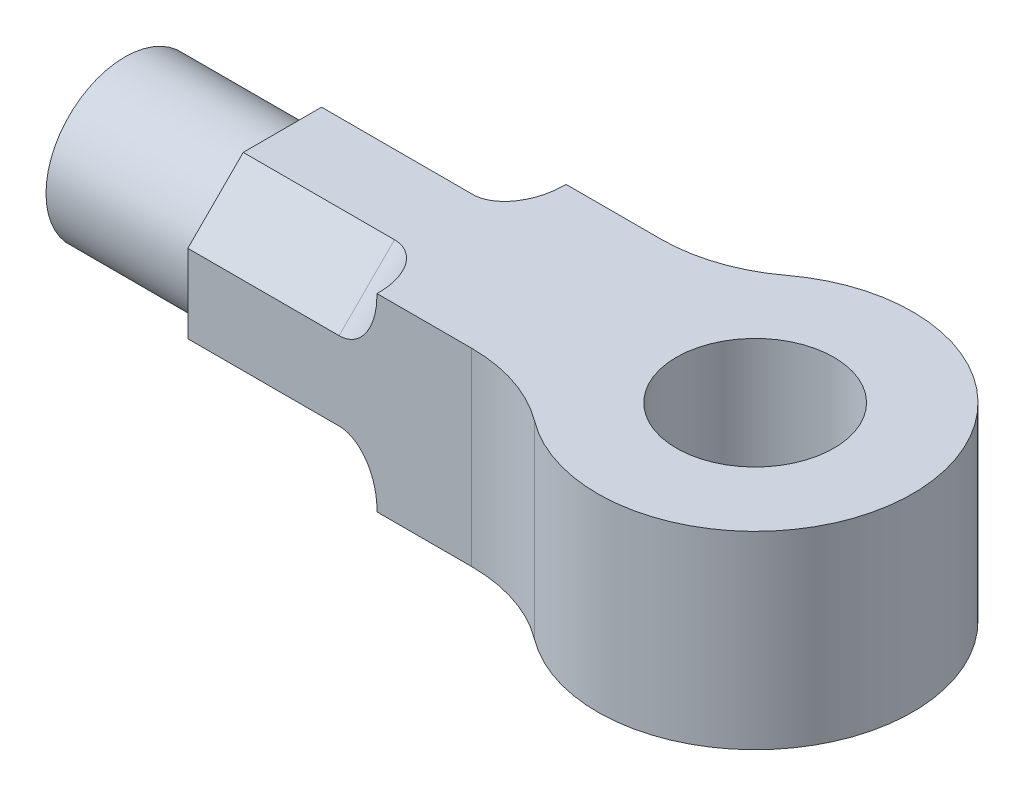
SolidWorks part; units mm, degrees
ref_plane "Front Plane" through (0, 0, 0) normal (0, 0, 1) x (1, 0, 0)
ref_plane "Top Plane" through (0, 0, 0) normal (0, 1, 0) x (1, 0, 0)
ref_plane "Right Plane" through (0, 0, 0) normal (1, 0, 0) x (0, 0, -1)
sketch "Sketch1" plane through (0, 0, 0) normal (0, 0, 1) x (1, 0, 0)
  line L1 (0, 60) -> (-200, 60)
  line L2 (0, 60) -> (0, 0)
  line L3 (0, 0) -> (-200, 0)
  line L4 (-200, 60) -> (-200, 0)
  dimension "D1" = 200
  dimension "D2" = 60
extrude "Boss-Extrude1" add sketch "Sketch1" along normal blind 60
sketch "Sketch2" plane through (0, 60, 0) normal (0, 1, 0) x (1, 0, 0)
  line L0 (0, -60) -> (0, 0) construction
  line L1 (-200, -60) -> (-200, 0) construction
  circle A0 centre (-50, -30) radius 50
  circle A1 centre (-50, -30) radius 25
  point P8 (-200, -30)
  dimension "D1" = 100
  dimension "D2" = 50
extrude "Boss-Extrude2" add sketch "Sketch2" against normal blind 60
sketch "Sketch3" plane through (0, 60, 0) normal (0, 1, 0) x (1, 0, 0)
  line L0 (0, -60) -> (-10, -60) construction
  line L1 (0, -60) -> (0, 0) construction
  line L2 (0, 0) -> (-10, 0) construction
  line L3 (0, -60) -> (-10, -60)
  line L4 (0, -60) -> (0, 0)
  line L5 (0, 0) -> (-10, 0)
  circle A1 centre (-50, -30) radius 25
  circle A2 centre (-50, -30) radius 25
  circle A3 centre (-50, -30) radius 50
  circle A4 centre (-50, -30) radius 50
  line M3 (0, 0) -> (-10, 0)
  line M9 (-10, -60) -> (0, -60)
  line M10 (0, -60) -> (0, 0)
  dimension "D1" = 0
  dimension "D2" = 0
extrude "Cut-Extrude1" cut sketch "Sketch3" against normal blind 60 contours A2 | A4 L4 M3 | A4 M9 M10
sketch "Sketch4" plane through (-200, 0, 0) normal (-1, 0, 0) x (0, 0, 1)
  line L0 (0, 0) -> (0, 60) construction
  line L1 (60, 60) -> (0, 60) construction
  circle A0 centre (30, 30) radius 25
  point P5 (0, 30)
  point P8 (30, 60)
  dimension "D1" = 50
extrude "Boss-Extrude3" add sketch "Sketch4" along normal blind 50
sketch "Sketch5" plane through (-200, 0, 0) normal (-1, 0, 0) x (0, 0, 1)
  line L0 (60, 60) -> (0, 60) construction
  line L1 (17.5736, 60) -> (0, 42.4264)
  line L2 (0, 42.4264) -> (0, 17.5736)
  line L3 (0, 17.5736) -> (17.5736, 0)
  line L4 (17.5736, 0) -> (42.4264, 0)
  line L5 (42.4264, 0) -> (60, 17.5736)
  line L6 (60, 17.5736) -> (60, 42.4264)
  line L7 (60, 42.4264) -> (42.4264, 60)
  line L8 (42.4264, 60) -> (17.5736, 60)
  line L9 (60, 60) -> (60, 0) construction
  line L10 (60, 0) -> (0, 0) construction
  line L11 (0, 60) -> (0, 0) construction
  line L12 (60, 60) -> (60, 0)
  line L13 (60, 0) -> (0, 0)
  line L14 (0, 60) -> (0, 0)
  line L15 (60, 60) -> (0, 60)
  line M3 (0, 60) -> (0, 0)
  line M4 (0, 0) -> (60, 0)
  line M5 (60, 0) -> (60, 60)
  line M6 (60, 60) -> (0, 60)
extrude "Cut-Extrude2" cut sketch "Sketch5" against normal blind 60 contours L7 M5 M6 | L1 M6 M3 | L3 M3 M4 | L5 M4 M5
fillet "Fillet1" radius 12 4 edges at (-140, 8.7868, 8.7868) (-140, 8.7868, 51.2132) (-140, 51.2132, 8.7868) (-140, 51.2132, 51.2132)
fillet "Fillet2" radius 50 2 edges at (-90, 30, 0) (-90, 30, 60)
